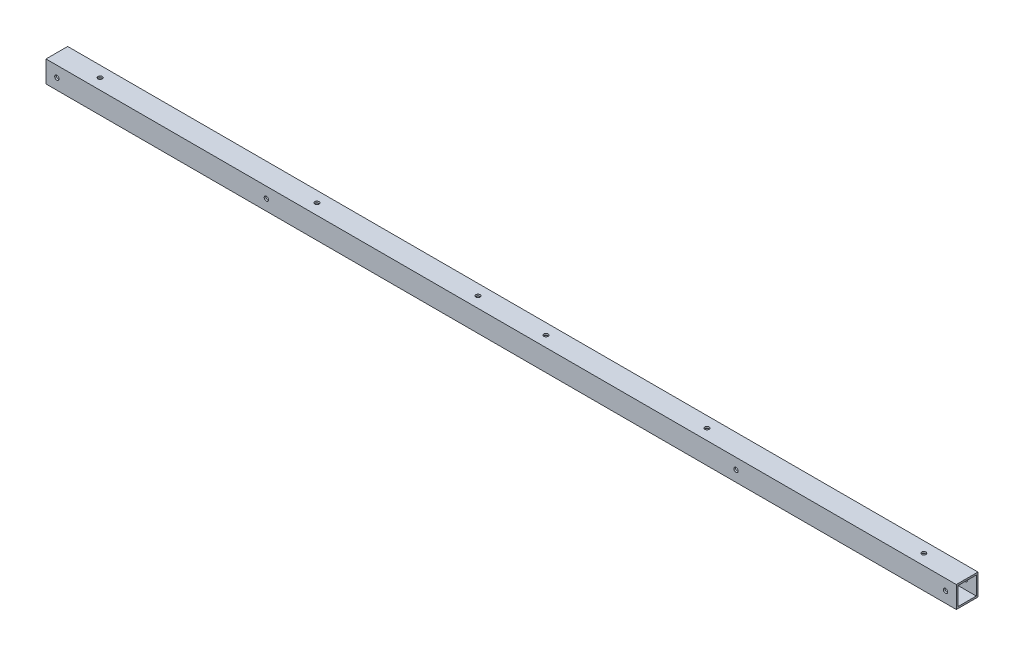
SolidWorks part; units mm, degrees
ref_plane "正面" through (0, 0, 0) normal (0, 0, 1) x (1, 0, 0)
ref_plane "平面" through (0, 0, 0) normal (0, 1, 0) x (1, 0, 0)
ref_plane "右側面" through (0, 0, 0) normal (1, 0, 0) x (0, 0, -1)
sketch "ｽｹｯﾁ1" plane through (0, 0, 0) normal (0, 0, 1) x (1, 0, 0)
  line L0 (0, 7.5) -> (630, 7.5) construction
  line L1 (0, 0) -> (630, 0)
  line L2 (0, 0) -> (0, 15)
  line L3 (0, 15) -> (630, 15)
  line L4 (630, 0) -> (630, 15)
  circle A0 centre (7.5, 7.5) radius 1.5
  circle A1 centre (622.5, 7.5) radius 1.5
  circle A2 centre (152.5, 7.5) radius 1.5
  circle A3 centre (477.5, 7.5) radius 1.5
  dimension "D3" = 7.5
  dimension "D4" = 7.5
  dimension "D5" = 3
  dimension "D6" = 145
  dimension "D7" = 145
  dimension "D1" = 15
  dimension "D2" = 630
extrude "ﾎﾞｽ - 押し出し1" add sketch "ｽｹｯﾁ1" along normal blind 15
sketch "ｽｹｯﾁ3" plane through (0, 15, 0) normal (0, 1, 0) x (1, 0, 0)
  line L0 (0, -7.5) -> (630, -7.5) construction
  line L1 (0, -15) -> (0, 0) construction
  line L2 (630, -15) -> (630, 0) construction
  circle A0 centre (30, -7.5) radius 1.5
  circle A1 centre (600, -7.5) radius 1.5
  circle A2 centre (180, -7.5) radius 1.5
  circle A3 centre (450, -7.5) radius 1.5
  dimension "D1" = 3
  dimension "D2" = 30
  dimension "D3" = 3
  dimension "D4" = 30
  dimension "D5" = 150
  dimension "D6" = 150
extrude "ｶｯﾄ - 押し出し1" cut sketch "ｽｹｯﾁ3" against normal through all
sketch "ｽｹｯﾁ4" plane through (630, 0, 0) normal (1, 0, 0) x (0, 0, -1)
  line L0 (-7.5, 15) -> (-7.5, 0) construction
  line L1 (-15, 15) -> (0, 15) construction
  line L2 (-15, 0) -> (0, 0) construction
  line L3 (-15, 0) -> (-15, 15) construction
  line L4 (-13.8, 1.2) -> (-1.2, 1.2)
  line L5 (-13.8, 1.2) -> (-13.8, 13.8)
  line L6 (-13.8, 13.8) -> (-1.2, 13.8)
  line L7 (-1.2, 1.2) -> (-1.2, 13.8)
  line L8 (-13.8, 1.2) -> (-1.2, 13.8) construction
  line L9 (-13.8, 13.8) -> (-1.2, 1.2) construction
  point P6 (-7.5, 7.5)
  dimension "D1" = 1.2
  dimension "D2" = 1.2
extrude "ｶｯﾄ - 押し出し2" cut sketch "ｽｹｯﾁ4" against normal through all
sketch "ｽｹｯﾁ5" plane through (0, 15, 0) normal (0, 1, 0) x (1, 0, 0)
  line L0 (315, 0) -> (315, -15) construction
  line L1 (630, 0) -> (0, 0) construction
  line L2 (630, -15) -> (0, -15) construction
  line L3 (291.5, -7.5) -> (338.5, -7.5) construction
  circle A0 centre (291.5, -7.5) radius 1.5
  circle A1 centre (338.5, -7.5) radius 1.5
  point P9 (315, -7.5)
  dimension "D1" = 3
  dimension "D2" = 47
extrude "ｶｯﾄ - 押し出し3" cut sketch "ｽｹｯﾁ5" against normal through all
